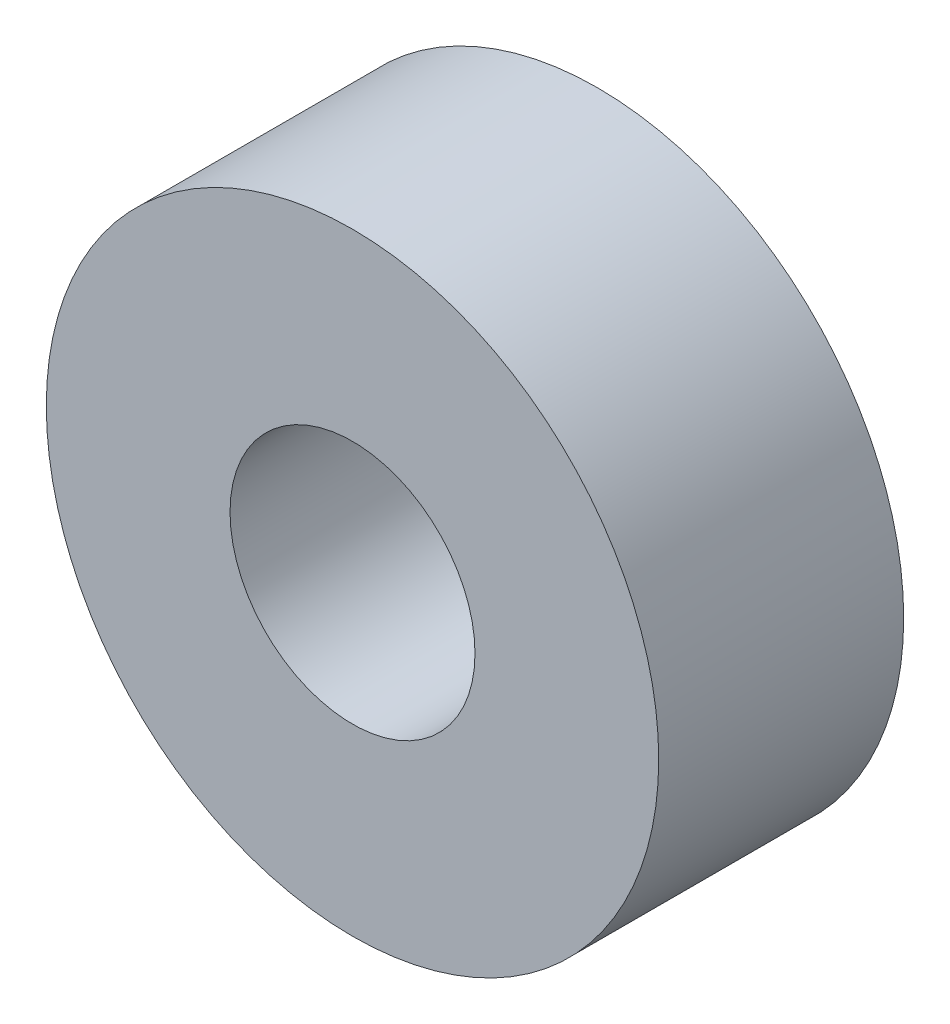
SolidWorks part; units mm, degrees
ref_plane "前视基准面" through (0, 0, 0) normal (0, 0, 1) x (1, 0, 0)
ref_plane "上视基准面" through (0, 0, 0) normal (0, 1, 0) x (1, 0, 0)
ref_plane "右视基准面" through (0, 0, 0) normal (1, 0, 0) x (0, 0, -1)
other "Configuration Table"
sketch "草图1" plane through (0, 0, 0) normal (0, 0, 1) x (1, 0, 0)
  circle A0 centre (0, 0) radius 2
  circle A1 centre (0, 0) radius 5
  dimension "D1" = 4
  dimension "D2" = 10
extrude "凸台-拉伸1" add sketch "草图1" along normal blind 4
